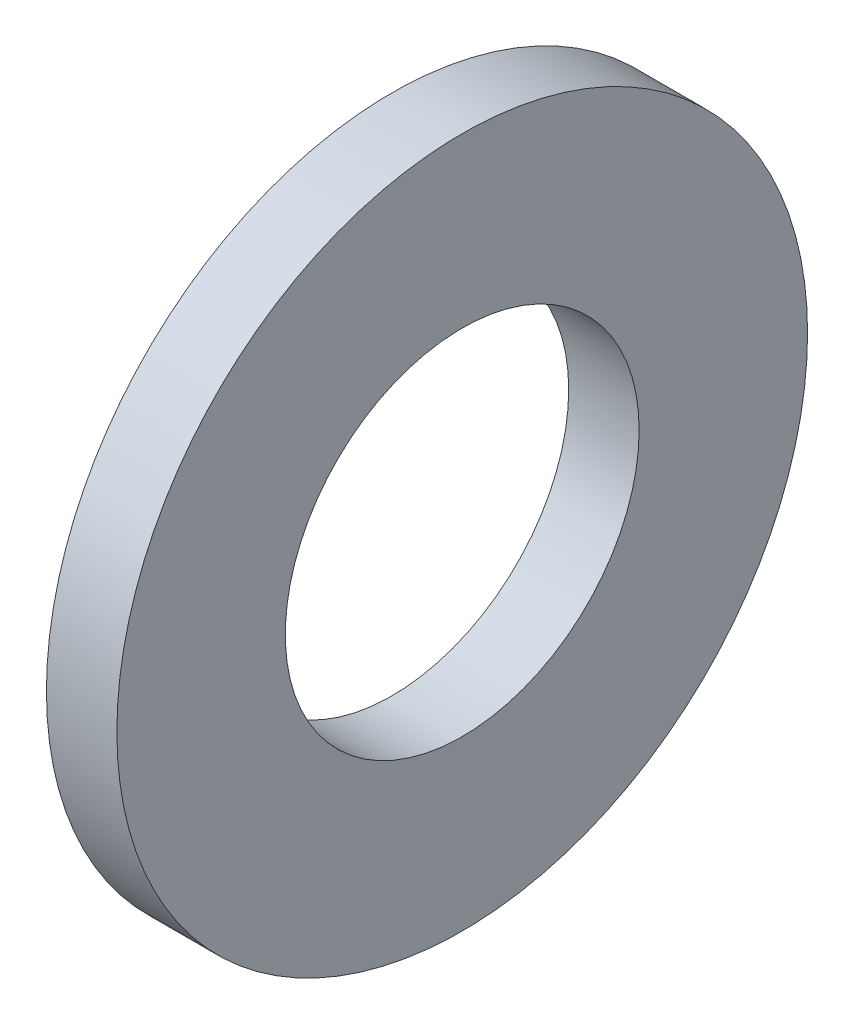
SolidWorks part; units mm, degrees
ref_plane "Plane1" through (0, 0, 0) normal (0, 0, 1) x (1, 0, 0)
ref_plane "Plane2" through (0, 0, 0) normal (0, 1, 0) x (1, 0, 0)
ref_plane "Plane3" through (0, 0, 0) normal (1, 0, 0) x (0, 0, -1)
sketch "Sketch1" plane through (0, 0, 0) normal (1, 0, 0) x (0, 0, -1)
  circle A0 centre (0, 0) radius 3.015
  circle A1 centre (0, 0) radius 5.885
  dimension "OutsideDia" = 11.77
  dimension "InsideDia" = 6.03
extrude "Base-Extrude" add sketch "Sketch1" along normal blind 1.2
